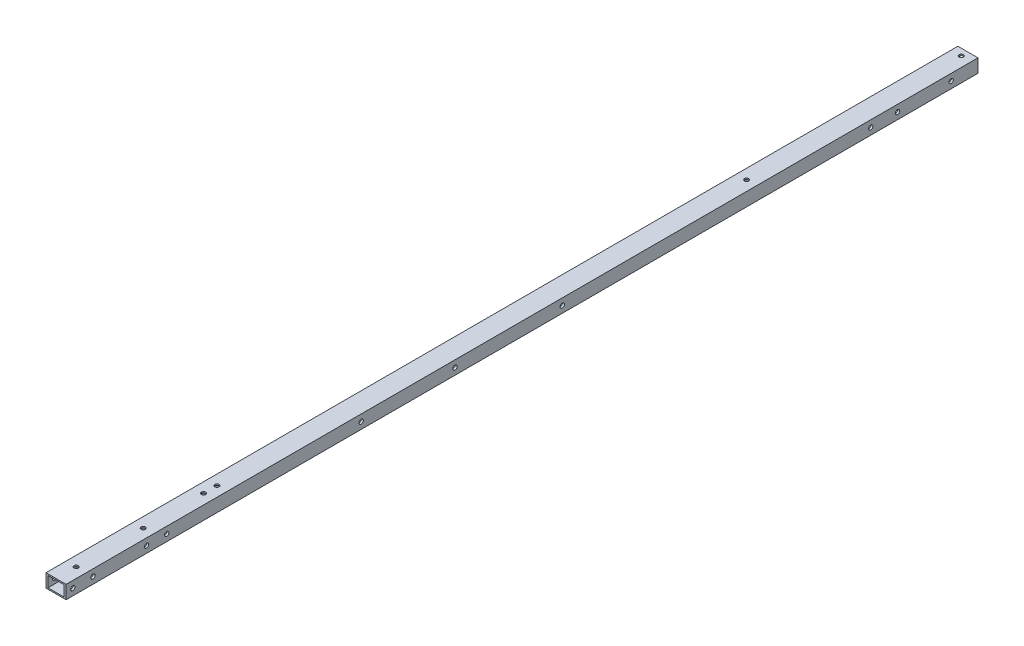
SolidWorks part; units mm, degrees
ref_plane "正面" through (0, 0, 0) normal (0, 0, 1) x (1, 0, 0)
ref_plane "平面" through (0, 0, 0) normal (0, 1, 0) x (1, 0, 0)
ref_plane "右側面" through (0, 0, 0) normal (1, 0, 0) x (0, 0, -1)
sketch "ｽｹｯﾁ1" plane through (0, 0, 0) normal (0, 0, 1) x (1, 0, 0)
  line L1 (-7.5, -5) -> (7.5, -5)
  line L2 (-7.5, -5) -> (-7.5, 5)
  line L3 (-7.5, 5) -> (7.5, 5)
  line L4 (7.5, -5) -> (7.5, 5)
  line L5 (-7.5, -5) -> (7.5, 5) construction
  line L6 (-7.5, 5) -> (7.5, -5) construction
  line L7 (-6, -4) -> (6, -4)
  line L8 (-6, -4) -> (-6, 4)
  line L9 (-6, 4) -> (6, 4)
  line L10 (6, -4) -> (6, 4)
  line L11 (-6, -4) -> (6, 4) construction
  line L12 (-6, 4) -> (6, -4) construction
  point P0 (0, 0)
  point P6 (0, 0)
  dimension "D1" = 1
  dimension "D2" = 15
  dimension "D3" = 10
extrude "ﾎﾞｽ - 押し出し1" add sketch "ｽｹｯﾁ1" along normal blind 40
sketch "ｽｹｯﾁ2" plane through (7.5, 0, 0) normal (1, 0, 0) x (0, 0, -1)
  line L0 (-40, -5) -> (0, -5) construction
  line L1 (0, -5) -> (0, 5) construction
  circle A0 centre (-20, 0) radius 1.6
  dimension "D1" = 3.2
  dimension "D2" = 5
  dimension "D3" = 20
extrude "ｶｯﾄ - 押し出し1" cut sketch "ｽｹｯﾁ2" against normal through all
sketch "ｽｹｯﾁ4" plane through (-7.5, 0, 0) normal (-1, 0, 0) x (0, 0, 1)
  line L1 (40, 5) -> (0, 5) construction
  line L2 (0, 5) -> (0, -5) construction
  circle A0 centre (35, 0) radius 1.6
  dimension "D1" = 3.2
  dimension "D2" = 35
  dimension "D3" = 5
extrude "ｶｯﾄ - 押し出し3" cut sketch "ｽｹｯﾁ4" against normal through all
sketch "ｽｹｯﾁ5" plane through (0, 5, 0) normal (0, 1, 0) x (1, 0, 0)
  line L1 (-7.5, -40) -> (-7.5, 0) construction
  line L2 (7.5, 0) -> (-7.5, 0) construction
  circle A0 centre (0, -25) radius 1.6
  dimension "D1" = 3.2
  dimension "D2" = 25
  dimension "D3" = 7.5
extrude "ｶｯﾄ - 押し出し4" cut sketch "ｽｹｯﾁ5" against normal through all
mirror "ﾐﾗｰ1" about plane through (0, 0, 0) normal (0, 0, -1) of "ｶｯﾄ - 押し出し4", "ｶｯﾄ - 押し出し3", "ｶｯﾄ - 押し出し1", "ﾎﾞｽ - 押し出し1"
sketch "ｽｹｯﾁ6" plane through (0, 0, -40) normal (0, 0, -1) x (-1, 0, 0)
  line L1 (-7.5, -5) -> (7.5, -5)
  line L2 (-7.5, -5) -> (-7.5, 5)
  line L3 (-7.5, 5) -> (7.5, 5)
  line L4 (7.5, -5) -> (7.5, 5)
  line L5 (-6, -4) -> (6, -4)
  line L6 (-6, -4) -> (-6, 4)
  line L7 (-6, 4) -> (6, 4)
  line L8 (6, -4) -> (6, 4)
extrude "ﾎﾞｽ - 押し出し2" add sketch "ｽｹｯﾁ6" along normal blind 600
sketch "ｽｹｯﾁ7" plane through (0, -5, 0) normal (0, -1, 0) x (-1, 0, 0)
  line L0 (-7.5, 640) -> (7.5, 640) construction
  line L1 (7.5, -40) -> (7.5, 640) construction
  line L2 (7.5, -40) -> (-7.5, -40) construction
  line L3 (-7.5, -40) -> (-7.5, 640) construction
  circle A0 centre (0, 635) radius 1.6
  circle A1 centre (0, 80) radius 1.6
  circle A2 centre (0, 70) radius 1.6
  circle A3 centre (0, 475) radius 1.6
  circle A4 centre (0, -25) radius 1.6 construction
  dimension "D1" = 3.2
  dimension "D2" = 3.2
  dimension "D3" = 5
  dimension "D4" = 7.5
  dimension "D5" = 7.5
  dimension "D6" = 110
  dimension "D7" = 10
  dimension "D8" = 3.2
  dimension "D9" = 7.5
  dimension "D10" = 3.2
  dimension "D11" = 7.5
  dimension "D12" = 500
extrude "ｶｯﾄ - 押し出し5" cut sketch "ｽｹｯﾁ7" against normal through all
sketch "ｽｹｯﾁ8" plane through (7.5, 0, 0) normal (1, 0, 0) x (0, 0, -1)
  line L0 (640, 5) -> (640, -5) construction
  line L1 (-40, -5) -> (640, -5) construction
  line L2 (-40, 5) -> (640, 5) construction
  line L3 (-40, -5) -> (-40, 5) construction
  circle A0 centre (330, 0) radius 1.6
  circle A1 centre (580, 0) radius 1.6
  circle A2 centre (180, 0) radius 1.6
  circle A3 centre (250, 0) radius 1.6
  circle A4 centre (560, 0) radius 1.6
  circle A5 centre (620, 0) radius 1.6
  dimension "D1" = 3.2
  dimension "D2" = 3.2
  dimension "D3" = 60
  dimension "D4" = 5
  dimension "D5" = 250
  dimension "D6" = 5
  dimension "D7" = 3.2
  dimension "D9" = 3.2
  dimension "D10" = 5
  dimension "D11" = 70
  dimension "D12" = 220
  dimension "D13" = 3.2
  dimension "D14" = 3.2
  dimension "D15" = 5
  dimension "D16" = 5
  dimension "D17" = 60
  dimension "D18" = 600
  dimension "D8" = 5
extrude "ｶｯﾄ - 押し出し6" cut sketch "ｽｹｯﾁ8" against normal through all
